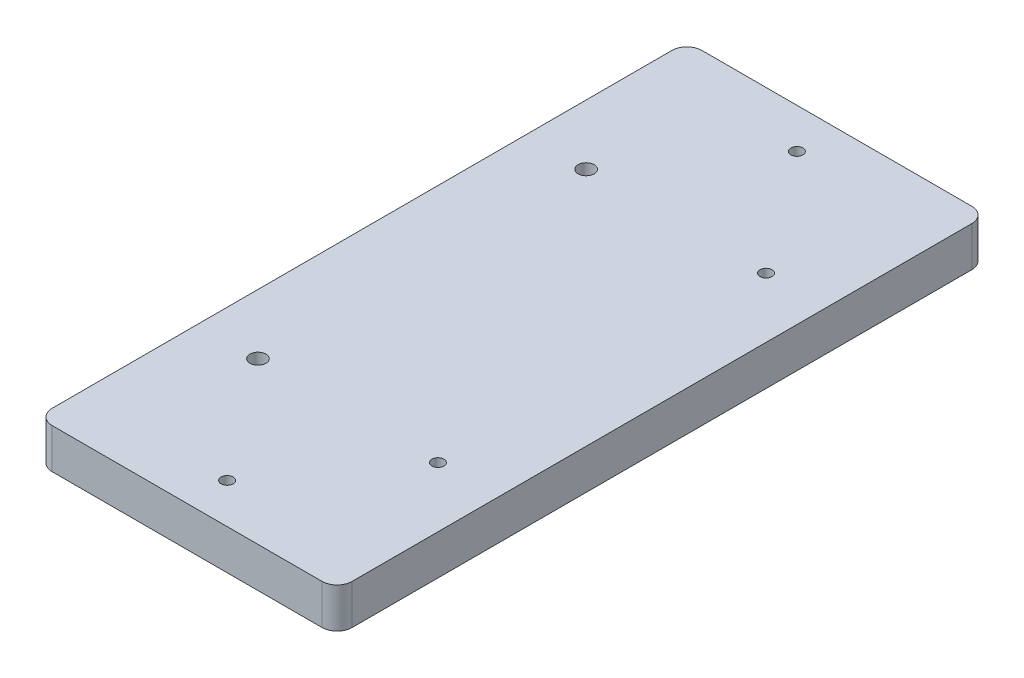
SolidWorks part; units mm, degrees
ref_plane "Front Plane" through (0, 0, 0) normal (0, 0, 1) x (1, 0, 0)
ref_plane "Top Plane" through (0, 0, 0) normal (0, 1, 0) x (1, 0, 0)
ref_plane "Right Plane" through (0, 0, 0) normal (1, 0, 0) x (0, 0, -1)
sketch "Sketch1" plane through (0, 0, 0) normal (0, 1, 0) x (1, 0, 0)
  line L0 (0, 0) -> (0, 130)
  line L1 (0, 130) -> (60, 130)
  line L2 (60, 130) -> (60, 0)
  line L3 (60, 0) -> (0, 0)
  circle A0 centre (12, 97.825) radius 1.6
  circle A1 centre (12, 32.175) radius 1.6
  circle A2 centre (48, 97.825) radius 1.2
  circle A3 centre (48, 32.175) radius 1.2
  circle A4 centre (30, 8) radius 1.2
  circle A5 centre (30, 122) radius 1.2
  point P4 (30, 0)
  dimension "D3" = 114
  dimension "D1" = 65.65
  dimension "D2" = 8
  dimension "D4" = 65.65
  dimension "D5" = 36
  dimension "D6" = 12
  dimension "D7" = 12
  dimension "D8" = 32.175
extrude "Boss-Extrude1" add sketch "Sketch1" along normal blind 8
fillet "Fillet1" radius 3 4 edges at (0, 4, -130) (60, 4, -130) (60, 4, 0) (0, 4, 0)
